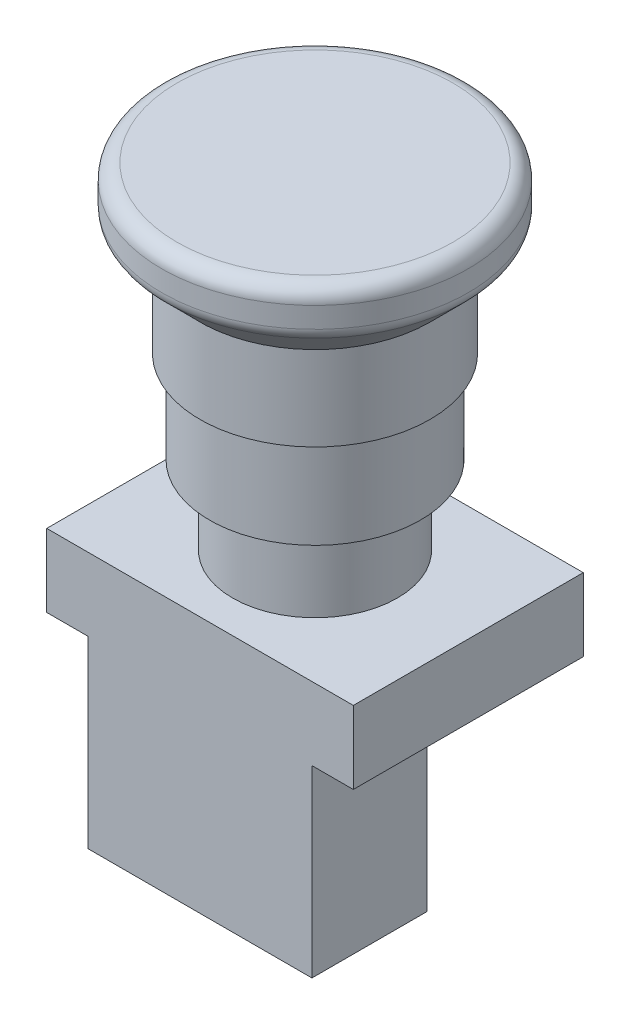
SolidWorks part; units mm, degrees
ref_plane "Alzado" through (0, 0, 0) normal (0, 0, 1) x (1, 0, 0)
ref_plane "Planta" through (0, 0, 0) normal (0, 1, 0) x (1, 0, 0)
ref_plane "Vista lateral" through (0, 0, 0) normal (1, 0, 0) x (0, 0, -1)
sketch "Croquis1" plane through (0, 0, 0) normal (0, 0, 1) x (1, 0, 0)
  line L0 (0, 0) -> (13.75, 0)
  line L1 (13.75, 0) -> (13.75, 12)
  line L2 (0, 0) -> (0, 12)
  line L3 (0, 12) -> (13.75, 12)
  dimension "D1" = 13.75
  dimension "D2" = 12
revolve "Revolución1" add sketch "Croquis1" angle 360 about L2
sketch "Croquis2" plane through (0, 0, 0) normal (0, 0, 1) x (1, 0, 0)
  line L0 (0, 12) -> (15, 12)
  line L1 (13.75, 12) -> (-13.75, 12) construction
  line L2 (15, 12) -> (15, 23)
  line L3 (15, 23) -> (19.4142, 27.4142)
  line L5 (0, 28) -> (0, 12)
  line L6 (0, 33.5281) -> (18, 33.5281)
  line L7 (20, 31.5281) -> (20, 28.8284)
  line L8 (0, 33.5281) -> (0, 28)
  arc A1 (18, 33.5281) -> (20, 31.5281) centre (18, 31.5281) cw
  arc A2 (19.4142, 27.4142) -> (20, 28.8284) centre (18, 28.8284) ccw
  point P9 (20, 28)
  point P12 (20, 33.5281)
  point P15 (20, 28)
  dimension "D5" = 20
  dimension "D6" = 2
  dimension "D1" = 15
  dimension "D2" = 11
  dimension "D3" = 20
  dimension "D4" = 5
revolve "Revolución2" add sketch "Croquis2" angle 360 about L5
sketch "Croquis3" plane through (0, 0, 0) normal (0, -1, 0) x (1, 0, 0)
  line L1 (-20, 15) -> (20, 15)
  line L2 (-20, 15) -> (-20, -15)
  line L3 (-20, -15) -> (20, -15)
  line L4 (20, 15) -> (20, -15)
  line L5 (-20, 15) -> (20, -15) construction
  line L6 (-20, -15) -> (20, 15) construction
  point P0 (0, 0)
  dimension "D1" = 40
  dimension "D2" = 30
sketch "Croquis5" plane through (0, 0, 0) normal (0, -1, 0) x (1, 0, 0)
  line L0 (-20, -15) -> (20, 15) construction
  circle A0 centre (0, 0) radius 10.75
  dimension "D1" = 21.5
extrude "Saliente-Extruir3" add sketch "Croquis5" along normal blind 10.3
sketch "Croquis8" plane through (0, -10.3, 0) normal (0, -1, 0) x (1, 0, 0)
  line L1 (-20, 15) -> (20, 15)
  line L2 (-20, 15) -> (-20, -15)
  line L3 (-20, -15) -> (20, -15)
  line L4 (20, 15) -> (20, -15)
  line L5 (-20, 15) -> (20, -15) construction
  line L6 (-20, -15) -> (20, 15) construction
  point P0 (0, 0)
  dimension "D1" = 40
  dimension "D2" = 30
extrude "Saliente-Extruir4" add sketch "Croquis8" along normal blind 9.5
sketch "Croquis9" plane through (0, -19.8, 0) normal (0, -1, 0) x (1, 0, 0)
  line L0 (0, 15) -> (0, -11.089) construction
  line L1 (20, 15) -> (-20, 15) construction
  line L3 (-14.6, 15) -> (14.6, 15)
  line L4 (-14.6, 15) -> (-14.6, 0)
  line L5 (-14.6, 0) -> (14.6, 0)
  line L6 (14.6, 15) -> (14.6, 0)
  line L7 (-14.6, 15) -> (14.6, 0) construction
  line L8 (-14.6, 0) -> (14.6, 15) construction
  point P5 (0, 7.5)
  dimension "D1" = 15
  dimension "D2" = 29.2
extrude "Saliente-Extruir5" add sketch "Croquis9" along normal blind 24
